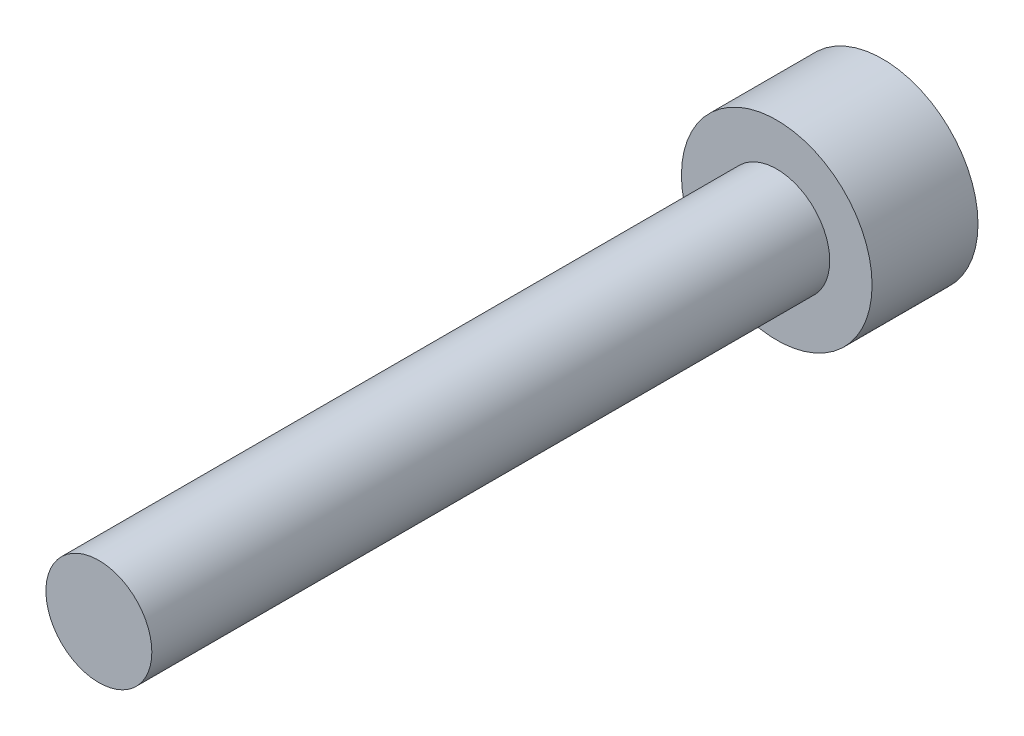
SolidWorks part; units mm, degrees
material "Acero aleado"
ref_plane "Alzado" through (0, 0, 0) normal (0, 0, 1) x (1, 0, 0)
ref_plane "Planta" through (0, 0, 0) normal (0, 1, 0) x (1, 0, 0)
ref_plane "Vista lateral" through (0, 0, 0) normal (1, 0, 0) x (0, 0, -1)
sketch "Croquis1" plane through (0, 0, 0) normal (0, 0, 1) x (1, 0, 0)
  circle A0 centre (0, 0) radius 2.25
  dimension "D1" = 4.5
extrude "Cabeza" add sketch "Croquis1" along normal blind 2.5 from offset 2.5
sketch "Croquis2" plane through (0, 0, 0) normal (0, 0, 1) x (1, 0, 0)
  circle A0 centre (0, 0) radius 1.25
  dimension "D1" = 2.5
extrude "Cuerpo" add sketch "Croquis2" along normal blind 16
sketch "Croquis3" plane through (0, 0, 0) normal (0, 0, 1) x (1, 0, 0)
  line L0 (1.1547, 0) -> (0.5774, 1)
  line L1 (0.5774, 1) -> (-0.5774, 1)
  line L2 (-0.5774, 1) -> (-1.1547, 0)
  line L3 (-1.1547, 0) -> (-0.5774, -1)
  line L4 (-0.5774, -1) -> (0.5774, -1)
  line L5 (0.5774, -1) -> (1.1547, 0)
  dimension "D1" = 1.1547
  dimension "D2" = 0.5774
  dimension "D3" = 1
  dimension "D4" = 0.5774
  dimension "D5" = 1
  dimension "D6" = 1.1547
  dimension "D7" = 0.5774
  dimension "D8" = 1
  dimension "D9" = 0.5774
  dimension "D10" = 1
extrude "Hexagono_interior" cut sketch "Croquis3" along normal blind 1.1 from offset 2.5
